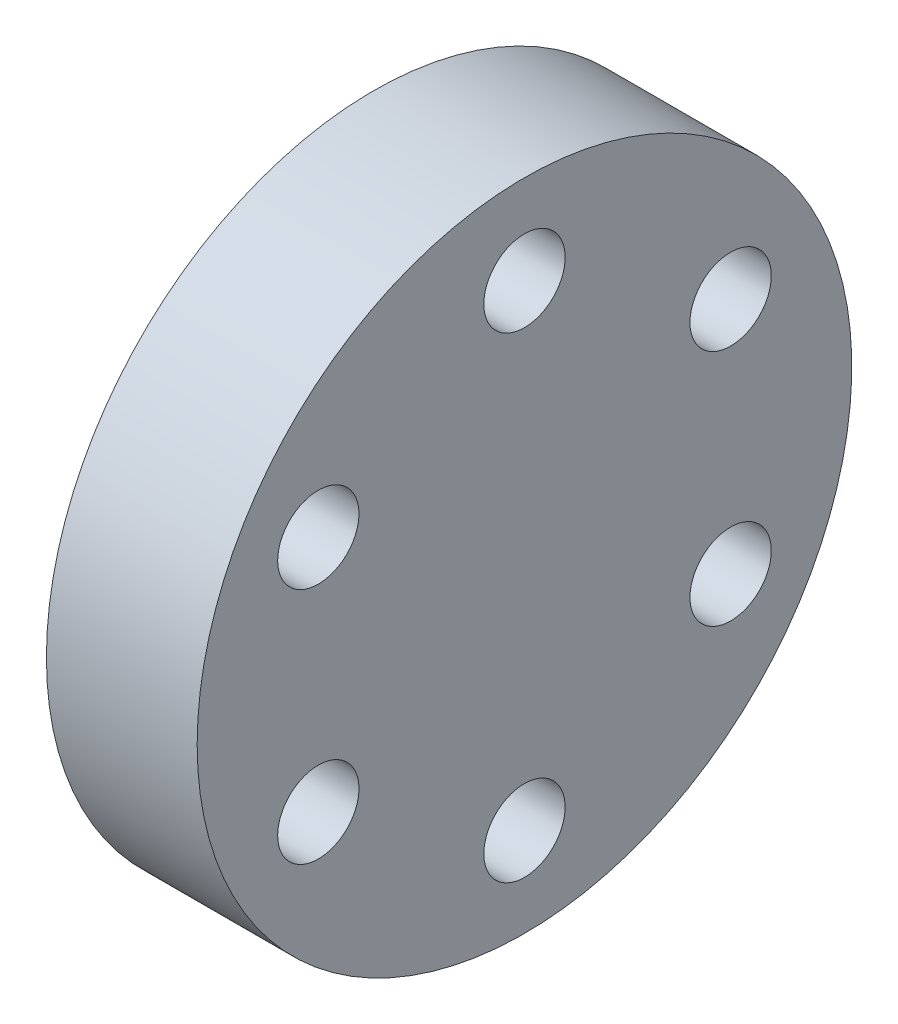
SolidWorks part; units mm, degrees
ref_plane "前视基准面" through (0, 0, 0) normal (0, 0, 1) x (1, 0, 0)
ref_plane "上视基准面" through (0, 0, 0) normal (0, 1, 0) x (1, 0, 0)
ref_plane "右视基准面" through (0, 0, 0) normal (1, 0, 0) x (0, 0, -1)
sketch "草图1" plane through (0, 0, 0) normal (1, 0, 0) x (0, 0, -1)
  circle A0 centre (0, 0) radius 16.5
  circle A1 centre (0, 0) radius 12 construction
  circle A2 centre (0, 12) radius 2.05
  circle A3 centre (10.3923, 6) radius 2.05
  circle A4 centre (10.3923, -6) radius 2.05
  circle A5 centre (0, -12) radius 2.05
  circle A6 centre (-10.3923, -6) radius 2.05
  circle A7 centre (-10.3923, 6) radius 2.05
  point P19 (0, 0)
  point P26 (0, 0)
  dimension "D1" = 33
  dimension "D2" = 24
  dimension "D3" = 4.1
  dimension "D4" = 6
extrude "凸台-拉伸1" add sketch "草图1" along normal blind 7.6
sketch "草图2" plane through (0, 0, 0) normal (-1, 0, 0) x (0, 0, 1)
  circle A0 centre (0, 0) radius 3.225
  dimension "D1" = 6.45
extrude "切除-拉伸1" cut sketch "草图2" against normal blind 4
